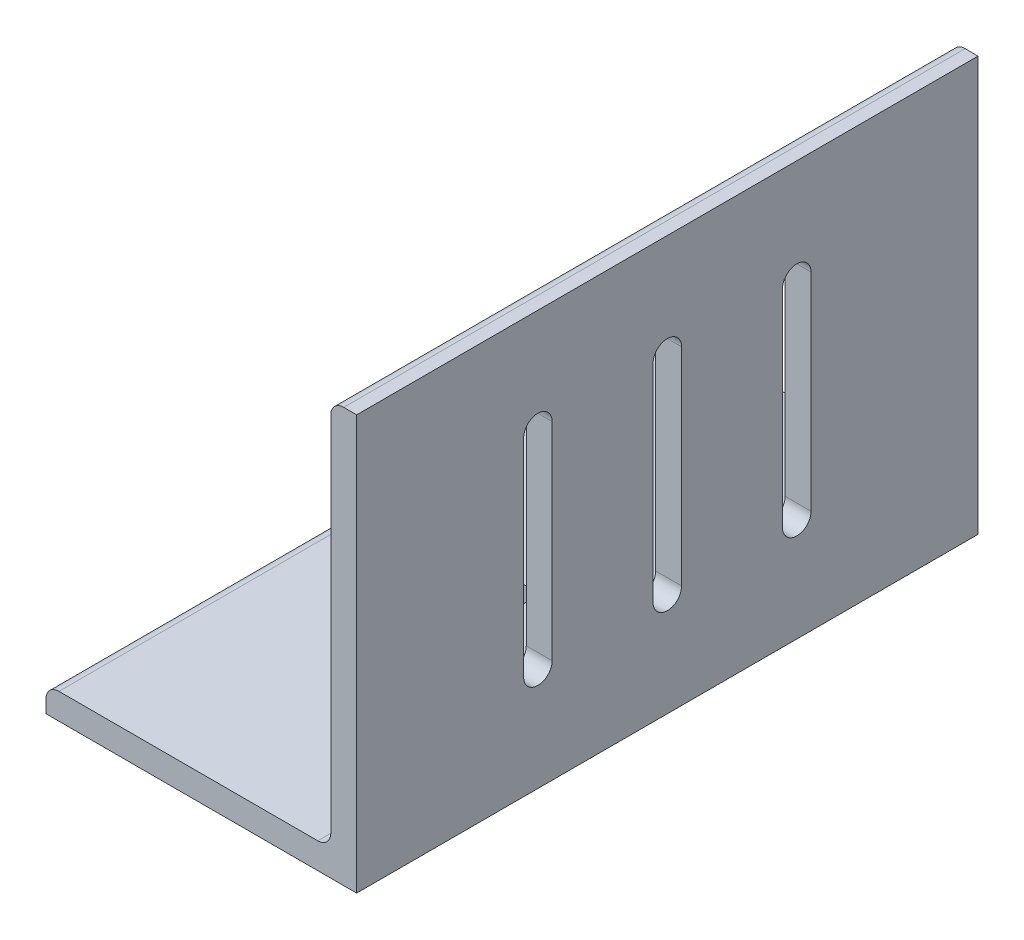
SolidWorks part; units mm, degrees
ref_plane "Front Plane" through (0, 0, 0) normal (0, 0, 1) x (1, 0, 0)
ref_plane "Top Plane" through (0, 0, 0) normal (0, 1, 0) x (1, 0, 0)
ref_plane "Right Plane" through (0, 0, 0) normal (1, 0, 0) x (0, 0, -1)
sketch "Sketch2" plane through (0, 0, 0) normal (0, 0, 1) x (1, 0, 0)
  line L0 (-38.1, 0) -> (38.1, 0)
  line L1 (38.1, 0) -> (38.1, 101.6)
  line L2 (38.1, 101.6) -> (31.75, 101.6) construction
  line L3 (31.75, 98.425) -> (31.75, 9.525)
  line L4 (28.575, 6.35) -> (-34.925, 6.35)
  line L5 (-38.1, 0) -> (-38.1, 6.35) construction
  line L6 (34.925, 101.6) -> (38.1, 101.6)
  line L7 (-38.1, 3.175) -> (-38.1, 0)
  arc A0 (31.75, 98.425) -> (34.925, 101.6) centre (34.925, 98.425) cw
  arc A1 (-38.1, 3.175) -> (-34.925, 6.35) centre (-34.925, 3.175) cw
  arc A2 (31.75, 9.525) -> (28.575, 6.35) centre (28.575, 9.525) cw
  dimension "Vert" = 101.6
  dimension "Horz" = 76.2
  dimension "Thickness" = 6.35
extrude "Boss-Extrude1" add sketch "Sketch2" along normal mid plane 152.4
ref_plane "Contact Plane 1" through (0, 6.35, 0) normal (0, 1, 0) x (1, 0, 0)
ref_plane "Contact Plane 2" through (31.75, 0, 0) normal (-1, 0, 0) x (0, 0, 1)
sketch "Sketch3" plane through (38.1, 0, 0) normal (1, 0, 0) x (0, 0, -1)
  line L0 (-31.75, 76.2) -> (-31.75, 25.4) construction
  line L1 (-28.25, 76.2) -> (-28.25, 25.4)
  line L2 (-35.25, 76.2) -> (-35.25, 25.4)
  line L3 (0, 0) -> (0, 101.6) construction
  line L4 (-76.2, 0) -> (76.2, 0) construction
  line L5 (-76.2, 101.6) -> (76.2, 101.6) construction
  line L6 (31.75, 76.2) -> (31.75, 25.4) construction
  line L7 (28.25, 76.2) -> (28.25, 25.4)
  line L8 (35.25, 76.2) -> (35.25, 25.4)
  line L9 (0, 76.2) -> (0, 25.4) construction
  line L10 (3.5, 76.2) -> (3.5, 25.4)
  line L11 (-3.5, 76.2) -> (-3.5, 25.4)
  arc A0 (-28.25, 76.2) -> (-35.25, 76.2) centre (-31.75, 76.2) ccw
  arc A1 (-35.25, 25.4) -> (-28.25, 25.4) centre (-31.75, 25.4) ccw
  arc A2 (28.25, 76.2) -> (35.25, 76.2) centre (31.75, 76.2) cw
  arc A3 (35.25, 25.4) -> (28.25, 25.4) centre (31.75, 25.4) cw
  arc A4 (3.5, 76.2) -> (-3.5, 76.2) centre (0, 76.2) ccw
  arc A5 (-3.5, 25.4) -> (3.5, 25.4) centre (0, 25.4) ccw
  point P2 (-31.75, 50.8)
  point P15 (31.75, 50.8)
  point P22 (0, 50.8)
  dimension "D1" = 3.5
  dimension "D3" = 31.75
  dimension "D5" = 3.5
  dimension "D2" = 50.8
  dimension "D4" = 50.8
  dimension "D6" = 50.8
  dimension "D7" = 50.8
extrude "Cut-Extrude1" cut sketch "Sketch3" against normal blind 10
sketch "Sketch4" plane through (0, 0, 0) normal (0, -1, 0) x (1, 0, 0)
  line L0 (-38.1, 76.2) -> (-38.1, -76.2) construction
  line L1 (-38.1, -76.2) -> (38.1, -76.2) construction
  circle A0 centre (0, 25.4) radius 3.5
  circle A1 centre (0, -25.4) radius 3.5
  circle A2 centre (0, 0) radius 3.5
  dimension "D1" = 7
  dimension "D2" = 7
  dimension "D3" = 38.1
  dimension "D4" = 76.2
extrude "Cut-Extrude2" cut sketch "Sketch4" against normal blind 10
